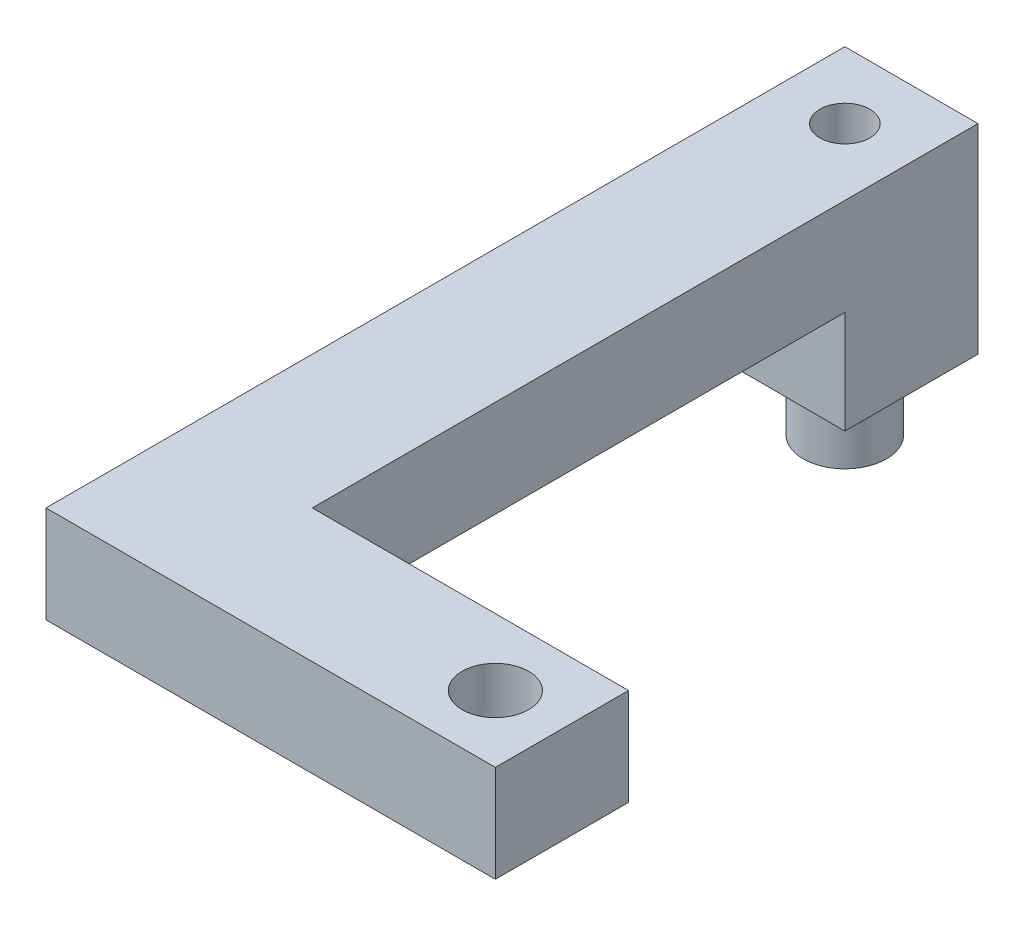
SolidWorks part; units mm, degrees
ref_plane "Plane Front" through (0, 0, 0) normal (0, 0, 1) x (1, 0, 0)
ref_plane "Plane Top" through (0, 0, 0) normal (0, 1, 0) x (1, 0, 0)
ref_plane "Plane Right" through (0, 0, 0) normal (1, 0, 0) x (0, 0, -1)
sketch "Sketch1" plane through (0, 0, 0) normal (0, 1, 0) x (1, 0, 0)
  line L1 (-6.1797, 4.7127) -> (20.8203, 4.7127)
  line L2 (-6.1797, 4.7127) -> (-6.1797, -43.2873)
  line L3 (-6.1797, -43.2873) -> (20.8203, -43.2873)
  line L4 (20.8203, 4.7127) -> (20.8203, -43.2873)
  dimension "D1" = 27
  dimension "D2" = 48
extrude "Extrude1" add sketch "Sketch1" along normal blind 12
sketch "Sketch2" plane through (0, 12, 0) normal (0, 1, 0) x (1, 0, 0)
  line L0 (-6.1797, 4.7127) -> (-6.1797, -43.2873) construction
  line L2 (20.8203, 4.7127) -> (-6.1797, 4.7127) construction
  line L3 (-6.1797, -43.2873) -> (20.8203, -43.2873) construction
  line L4 (20.8203, 4.7127) -> (1.8203, 4.7127)
  line L5 (20.8203, -43.2873) -> (20.8203, 4.7127) construction
  line L10 (20.8203, 4.7127) -> (20.8203, -35.2873)
  line L11 (20.8203, -35.2873) -> (1.8203, -35.2873)
  line L12 (1.8203, 4.7127) -> (1.8203, -35.2873)
  circle A0 centre (-2.1797, 0.7127) radius 1.5
  circle A1 centre (16.8203, -39.2873) radius 2
  dimension "D1" = 3
  dimension "D4" = 4
  dimension "D2" = 4
  dimension "D3" = 4
  dimension "D5" = 4
  dimension "D6" = 4
  dimension "D7" = 8
  dimension "D8" = 8
extrude "Extrude2" cut sketch "Sketch2" against normal through all
sketch "Sketch3" plane through (20.8203, 0, 0) normal (1, 0, 0) x (0, 0, -1)
  line L0 (-43.2873, 12) -> (-43.2873, 0) construction
  line L5 (-43.2873, 0) -> (-35.2873, 0) construction
  line L7 (4.7127, 12) -> (4.7127, 0) construction
  line L9 (-43.2873, 6.175) -> (-3.2873, 6.175)
  line L10 (-43.2873, 6.175) -> (-43.2873, 0)
  line L11 (-43.2873, 0) -> (-3.2873, 0)
  line L12 (-3.2873, 6.175) -> (-3.2873, 0)
  dimension "D1" = 8
  dimension "D5" = 0
  dimension "D6" = 0
  dimension "D8" = 6.175
extrude "Extrude3" cut sketch "Sketch3" against normal through all contours L10 L9 L12 L11
sketch "Sketch7" plane through (0, 0, 0) normal (0, -1, 0) x (1, 0, 0)
  circle A0 centre (-2.1797, -0.7127) radius 2.5
  dimension "D1" = 5
extrude "Extrude7" add sketch "Sketch7" along normal blind 4.2
